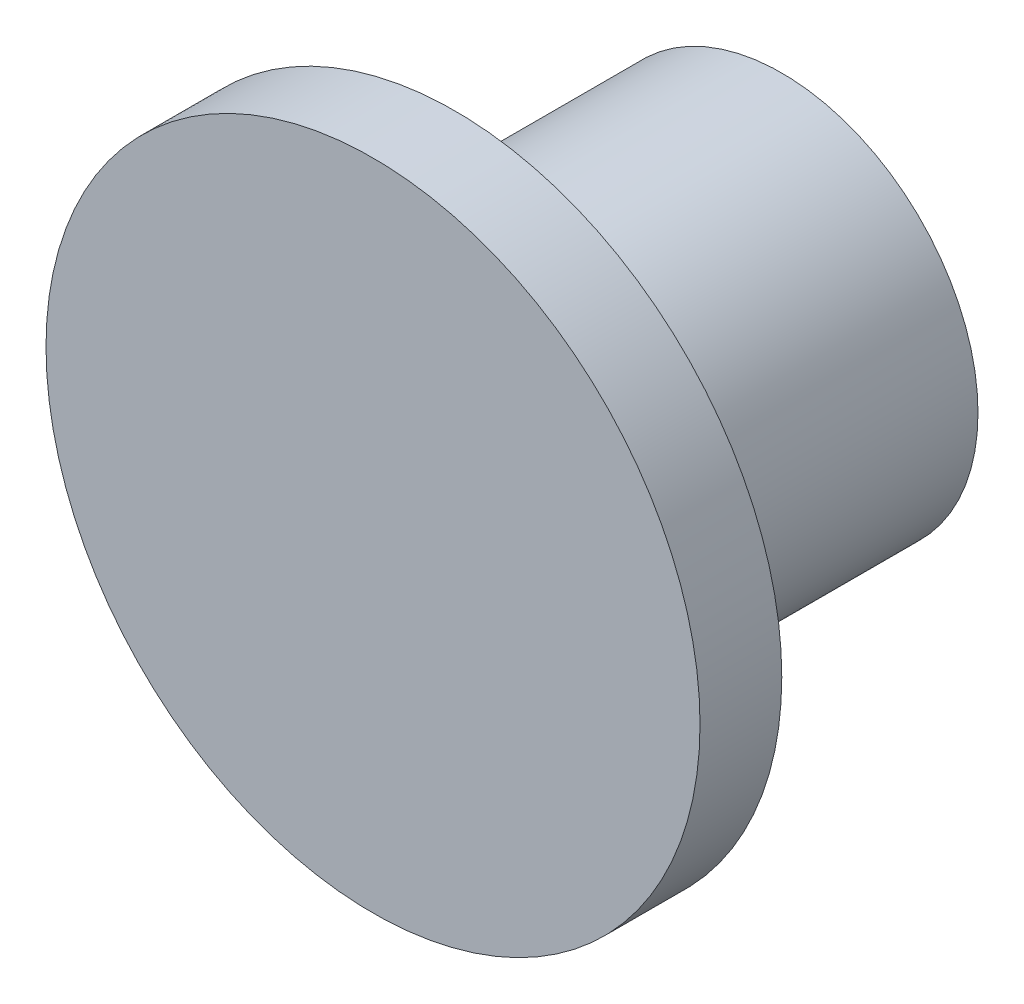
SolidWorks part; units mm, degrees
ref_plane "Front Plane" through (0, 0, 0) normal (0, 0, 1) x (1, 0, 0)
ref_plane "Top Plane" through (0, 0, 0) normal (0, 1, 0) x (1, 0, 0)
ref_plane "Right Plane" through (0, 0, 0) normal (1, 0, 0) x (0, 0, -1)
sketch "Sketch1" plane through (0, 0, 0) normal (0, 0, 1) x (1, 0, 0)
  circle A0 centre (0, 0) radius 20
  circle A1 centre (0, 0) radius 12
  dimension "D1" = 24
  dimension "D2" = 40
extrude "Boss-Extrude1" add sketch "Sketch1" along normal blind 5
sketch "Sketch2" plane through (0, 0, 5) normal (0, 0, 1) x (1, 0, 0)
  circle A0 centre (0, 0) radius 12
extrude "Boss-Extrude2" add sketch "Sketch2" against normal blind 25
